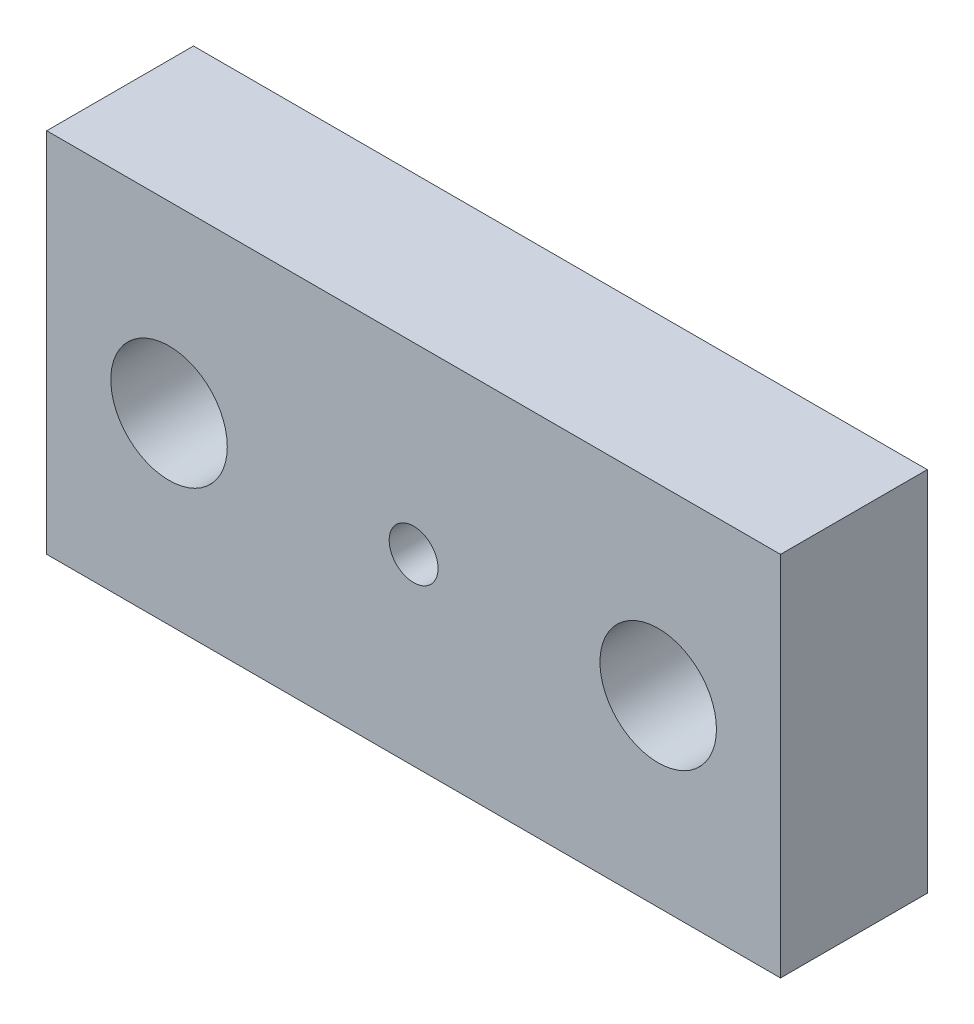
SolidWorks part; units mm, degrees
ref_plane "Front" through (0, 0, 0) normal (0, 0, 1) x (1, 0, 0)
ref_plane "Top" through (0, 0, 0) normal (0, 1, 0) x (1, 0, 0)
ref_plane "Right" through (0, 0, 0) normal (1, 0, 0) x (0, 0, -1)
sketch "Sketch1" plane through (0, 0, 0) normal (0, 0, 1) x (1, 0, 0)
  line L0 (-15, 0) -> (-10, 0) construction
  line L1 (-15, -7.5) -> (15, -7.5)
  line L2 (-15, -7.5) -> (-15, 7.5)
  line L3 (-15, 7.5) -> (15, 7.5)
  line L4 (15, -7.5) -> (15, 7.5)
  line L5 (-15, -7.5) -> (15, 7.5) construction
  line L6 (-15, 7.5) -> (15, -7.5) construction
  line L7 (-10, 0) -> (0, 0) construction
  line L8 (0, 0) -> (10, 0) construction
  line L9 (10, 0) -> (15, 0) construction
  circle A0 centre (0, 0) radius 1
  circle A1 centre (10, 0) radius 2.3813
  circle A2 centre (-10, 0) radius 2.3813
  point P0 (0, 0)
  dimension "D4" = 2
  dimension "D5" = 4.7625
  dimension "D1" = 30
  dimension "D2" = 15
  dimension "D3" = 20
extrude "Boss-Extrude1" add sketch "Sketch1" along normal blind 6
sketch "Sketch3" plane through (0, 0, 0) normal (0, 0, -1) x (-1, 0, 0)
  circle A0 centre (0, 0) radius 2.5
  dimension "D1" = 5
extrude "Cut-Extrude2" cut sketch "Sketch3" against normal blind 3
